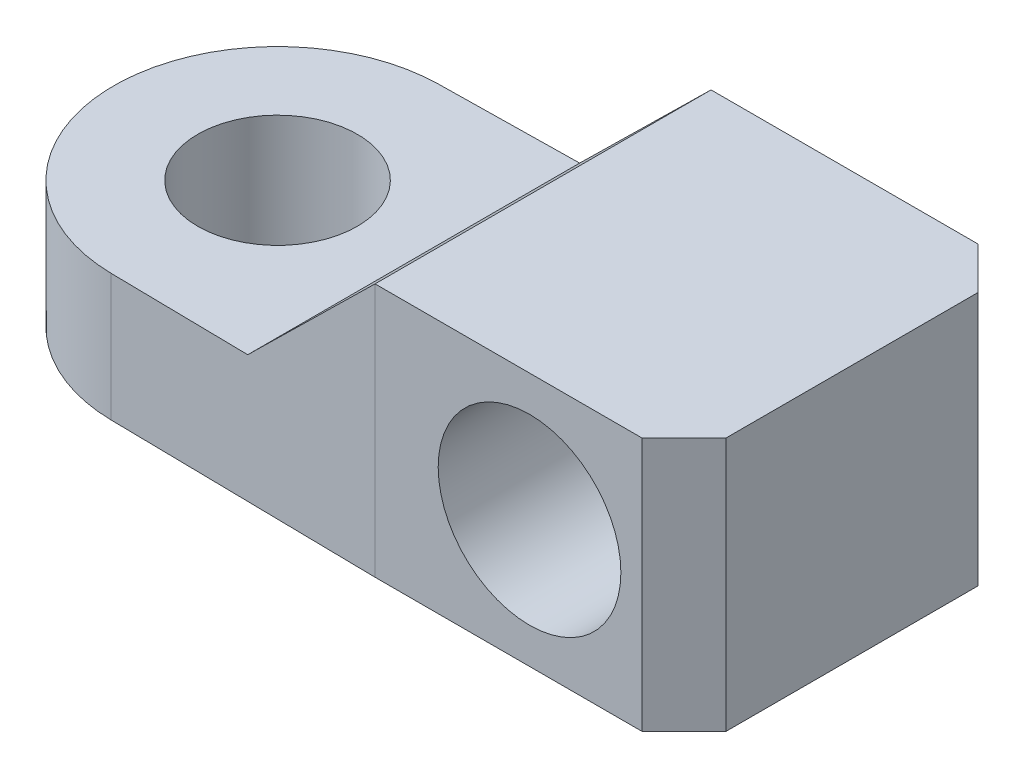
SolidWorks part; units mm, degrees
ref_plane "Front Plane" through (0, 0, 0) normal (0, 0, 1) x (1, 0, 0)
ref_plane "Top Plane" through (0, 0, 0) normal (0, 1, 0) x (1, 0, 0)
ref_plane "Right Plane" through (0, 0, 0) normal (1, 0, 0) x (0, 0, -1)
sketch "Sketch1" plane through (0, 0, 0) normal (0, 1, 0) x (1, 0, 0)
  line L0 (-0.0614, 3.8995) -> (6.322, 4)
  line L1 (6.322, 4) -> (13.678, 4)
  line L2 (13.678, 4) -> (13.678, -4)
  line L3 (13.678, -4) -> (6.322, -4)
  line L4 (6.322, -4) -> (-0.0614, -3.8995)
  line L5 (0, 0) -> (35.7724, 0) construction
  line L6 (10, -4) -> (10, 4) construction
  line L8 (9.322, -4) -> (10.678, -4) construction
  line L9 (9.322, -4) -> (9.322, 4) construction
  line L10 (9.322, 4) -> (10.678, 4) construction
  line L11 (10.678, -4) -> (10.678, 4) construction
  line L12 (9.322, -4) -> (10.678, 4) construction
  line L13 (9.322, 4) -> (10.678, -4) construction
  circle A0 centre (0, 0) radius 1.9
  arc A1 (-0.0614, 3.8995) -> (-0.0614, -3.8995) centre (0, 0) ccw
  point P6 (13.678, 0)
  point P14 (10, 0)
  point P18 (10, 0)
  dimension "D1" = 3.8
  dimension "D2" = 2
  dimension "D3" = 3
  dimension "D4" = 10
  dimension "D5" = 8
extrude "Boss-Extrude1" add sketch "Sketch1" along normal blind 6.05 contours A1 L4 L3 L2 L1 L0
sketch "Sketch2" plane through (0, 0, 0) normal (0, 0, 1) x (1, 0, 0)
  line L0 (10, 0) -> (10, 6.05) construction
  line L1 (13.678, 0) -> (6.322, 0) construction
  line L2 (13.678, 6.05) -> (6.322, 6.05) construction
  circle A0 centre (10, 3.025) radius 2.175
  dimension "D1" = 4.35
extrude "Cut-Extrude1" cut sketch "Sketch2" against normal blind 21 and the other way blind 19
chamfer "Chamfer2" distance 1 angle 45 4 edges at (13.678, 3.025, 4) (13.678, 3.025, -4) (13.678, 0, 0) (13.678, 6.05, 0)
sketch "Sketch3" plane through (0, 0, 0) normal (0, 0, 1) x (1, 0, 0)
  line L0 (-3.9, 3.025) -> (3.2419, 3.025)
  line L1 (-3.9, 6.05) -> (-3.9, 0) construction
  line L2 (3.2419, 3.025) -> (6.322, 6.05)
  line L3 (6.322, 6.05) -> (-0.0614, 6.05) construction
  line L4 (6.322, 6.05) -> (-3.9, 6.05)
  line L5 (-3.9, 6.05) -> (-3.9, 3.025)
  line L6 (6.322, 6.05) -> (6.322, 0) construction
  point P4 (5.2621, 6)
  point P13 (3.2419, 3)
extrude "Cut-Extrude2" cut sketch "Sketch3" against normal blind 10 and the other way blind 10
